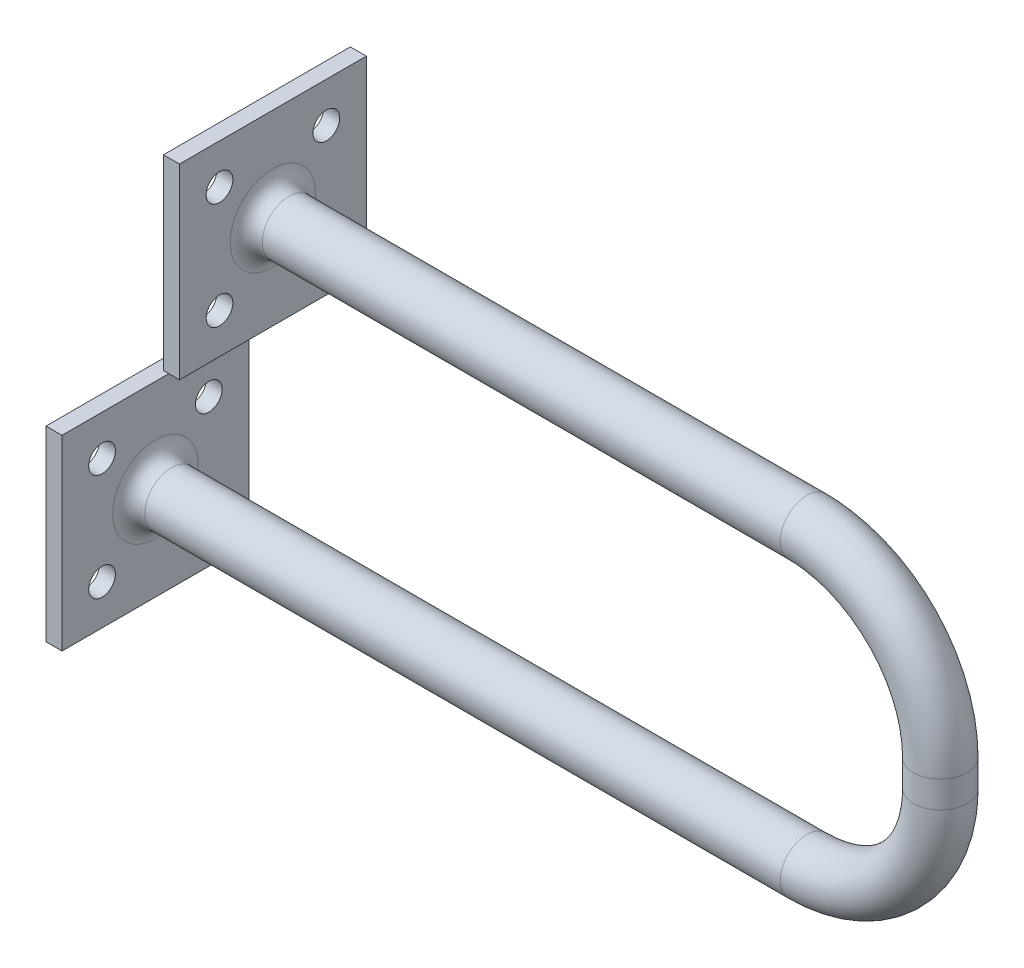
SolidWorks part; units mm, degrees
ref_plane "Front Plane" through (0, 0, 0) normal (0, 0, 1) x (1, 0, 0)
ref_plane "Top Plane" through (0, 0, 0) normal (0, 1, 0) x (1, 0, 0)
ref_plane "Right Plane" through (0, 0, 0) normal (1, 0, 0) x (0, 0, -1)
sketch "Sketch1" plane through (0, 0, 0) normal (1, 0, 0) x (0, 0, -1)
  line L1 (-17.5, -17.5) -> (17.5, -17.5)
  line L2 (-17.5, -17.5) -> (-17.5, 17.5)
  line L3 (-17.5, 17.5) -> (17.5, 17.5)
  line L4 (17.5, -17.5) -> (17.5, 17.5)
  line L5 (-17.5, -17.5) -> (17.5, 17.5) construction
  line L6 (-17.5, 17.5) -> (17.5, -17.5) construction
  point P0 (0, 0)
extrude "Boss-Extrude1" add sketch "Sketch1" along normal blind 3
sketch "Sketch2" plane through (3, 0, 0) normal (1, 0, 0) x (0, 0, -1)
  circle A0 centre (10, 10) radius 2.5
extrude "Cut-Extrude1" cut sketch "Sketch2" against normal through all
pattern_linear "LPattern1" count 2 spacing 20 along (0, 0, 1) count 2 spacing 20 along (0, -1, 0) of "Cut-Extrude1"
sketch "Sketch5" plane through (3, 0, 0) normal (1, 0, 0) x (0, 0, -1)
  line L0 (0, 6.2733) -> (0, 17.5) construction
sketch "Sketch6" plane through (0, 17.5, 0) normal (0, 1, 0) x (1, 0, 0)
  line L0 (0, 0) -> (10.5171, 0) construction
ref_plane "Plane1" through (0, 0, 0) normal (0, 0, 1) x (1, 0, 0)
sketch "Sketch8" plane through (0, 0, 0) normal (0, 0, 1) x (1, 0, 0)
  line L0 (0, 0) -> (125, 0)
  line L1 (150, 25) -> (150, 30)
  line L2 (125, 55) -> (25, 55)
  arc A0 (125, 0) -> (150, 25) centre (125, 25) ccw
  arc A1 (125, 55) -> (150, 30) centre (125, 30) cw
sketch "Sketch9" plane through (3, 0, 0) normal (1, 0, 0) x (0, 0, -1)
  circle A0 centre (0, 0) radius 5
sweep "Sweep1" add profiles "Sketch9" path "Sketch8"
sketch "Sketch10" plane through (25, 0, 0) normal (-1, 0, 0) x (0, 0, 1)
  line L1 (-17.5, 37.5) -> (17.5, 37.5)
  line L2 (-17.5, 37.5) -> (-17.5, 72.5)
  line L3 (-17.5, 72.5) -> (17.5, 72.5)
  line L4 (17.5, 37.5) -> (17.5, 72.5)
  line L5 (-17.5, 37.5) -> (17.5, 72.5) construction
  line L6 (-17.5, 72.5) -> (17.5, 37.5) construction
  point P0 (0, 55)
extrude "Boss-Extrude2" add sketch "Sketch10" along normal blind 3
sketch "Sketch11" plane through (22, 0, 0) normal (-1, 0, 0) x (0, 0, 1)
  line L0 (-17.5, 72.5) -> (17.5, 37.5) construction
  line L1 (-17.5, 37.5) -> (17.5, 72.5) construction
  circle A0 centre (9.9995, 64.9995) radius 2.5
extrude "Cut-Extrude2" cut sketch "Sketch11" against normal through all
pattern_linear "LPattern4" count 2 spacing 20 along (0, 0, -1) count 2 spacing 20 along (0, -1, 0) of "Cut-Extrude2"
fillet "Fillet1" radius 3 1 edges at (25, 55, -5)
fillet "Fillet2" radius 3 1 edges at (3, 0, -5)
